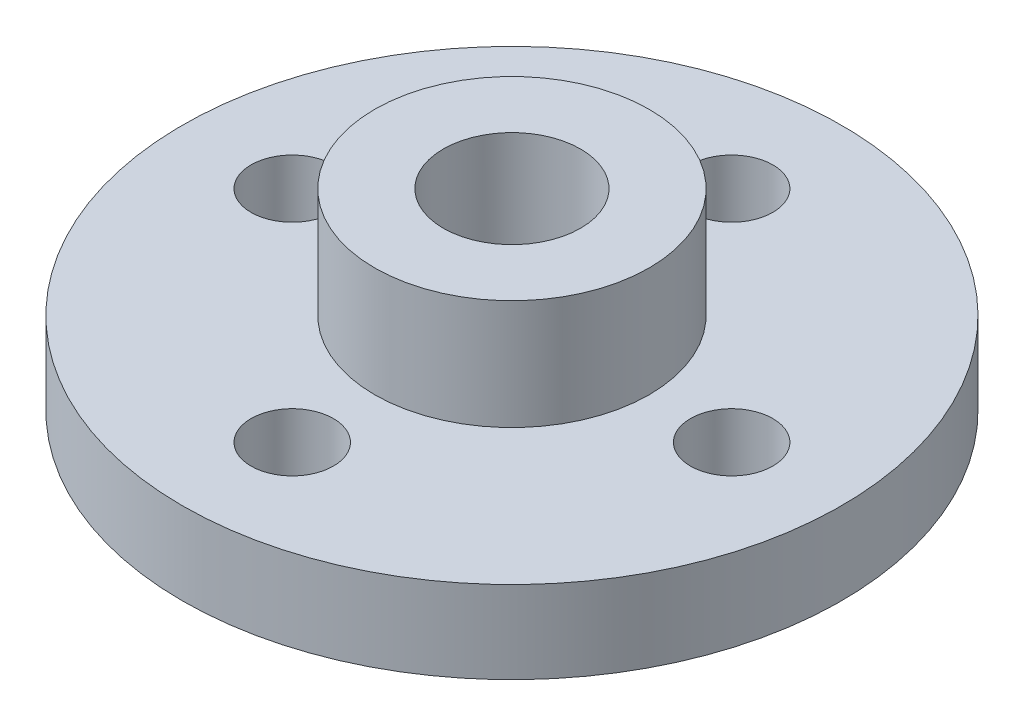
SolidWorks part; units mm, degrees
ref_plane "Plan de face" through (0, 0, 0) normal (0, 0, 1) x (1, 0, 0)
ref_plane "Plan de dessus" through (0, 0, 0) normal (0, 1, 0) x (1, 0, 0)
ref_plane "Plan de droite" through (0, 0, 0) normal (1, 0, 0) x (0, 0, -1)
sketch "Esquisse1" plane through (0, 0, 0) normal (0, 1, 0) x (1, 0, 0)
  circle A0 centre (0, 0) radius 12
extrude "Boss.-Extru.1" add sketch "Esquisse1" along normal blind 3
sketch "Esquisse2" plane through (0, 3, 0) normal (0, 1, 0) x (1, 0, 0)
  circle A0 centre (0, 0) radius 5
  circle A1 centre (0, 0) radius 2.5
  point P4 (0, 0)
extrude "Boss.-Extru.2" add sketch "Esquisse2" along normal blind 4
sketch "Esquisse3" plane through (0, 0, 0) normal (0, -1, 0) x (1, 0, 0)
  circle A0 centre (0, 0) radius 2.5
extrude "Enlèv. mat.-Extru.1" cut sketch "Esquisse3" against normal up to next
sketch "Esquisse4" plane through (0, 0, 0) normal (0, -1, 0) x (1, 0, 0)
  line L0 (0, 0) -> (0, 8) construction
  circle A0 centre (0, 0) radius 8
  circle A1 centre (0, 8) radius 1.5
  circle A2 centre (8, 0) radius 1.5
  circle A3 centre (0, -8) radius 1.5
  circle A4 centre (-8, 0) radius 1.5
extrude "Enlèv. mat.-Extru.2" cut sketch "Esquisse4" against normal up to next contours A0 A4 | A0 A4 | A1 L0 A0 | L0 A1 A0 | A0 A1 | A0 A2 | A0 A2 | A0 A3 | A0 A3
